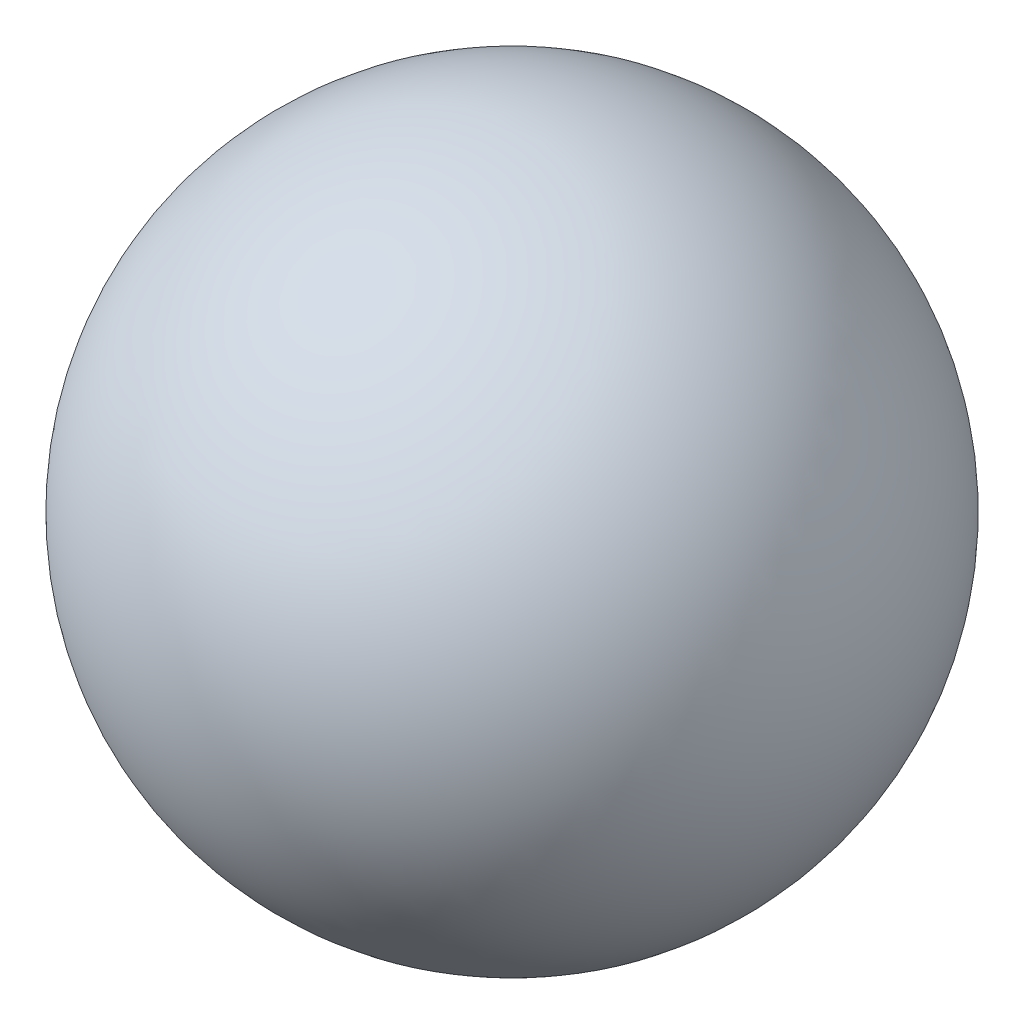
SolidWorks part; units mm, degrees
ref_plane "前视基准面" through (0, 0, 0) normal (0, 0, 1) x (1, 0, 0)
ref_plane "上视基准面" through (0, 0, 0) normal (0, 1, 0) x (1, 0, 0)
ref_plane "右视基准面" through (0, 0, 0) normal (1, 0, 0) x (0, 0, -1)
sketch "草图1" plane through (0, 0, 0) normal (0, 0, 1) x (1, 0, 0)
  line L0 (0, 21) -> (0, -21) construction
  arc A0 (0, -21) -> (0, 21) centre (0, 0) ccw
  dimension "D1" = 21
revolve "旋转1" add sketch "草图1" angle 360 about L0
